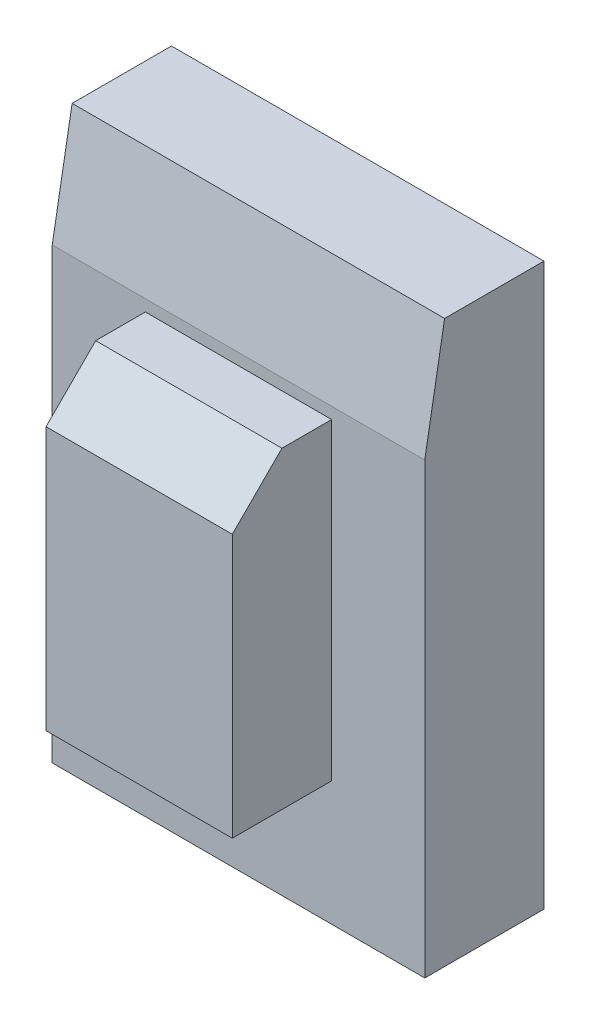
SolidWorks part; units mm, degrees
material "ABS"
ref_plane "Front Plane" through (0, 0, 0) normal (0, 0, 1) x (1, 0, 0)
ref_plane "Top Plane" through (0, 0, 0) normal (0, 1, 0) x (1, 0, 0)
ref_plane "Right Plane" through (0, 0, 0) normal (1, 0, 0) x (0, 0, -1)
sketch "Sketch1" plane through (0, 0, 0) normal (0, 0, 1) x (1, 0, 0)
  line L1 (0, 0) -> (9.525, 0)
  line L2 (0, 0) -> (0, -14.351)
  line L3 (0, -14.351) -> (9.525, -14.351)
  line L4 (9.525, 0) -> (9.525, -14.351)
  dimension "D1" = 14.351
  dimension "D2" = 9.525
extrude "Boss-Extrude1" add sketch "Sketch1" along normal blind 3.048
sketch "Sketch2" plane through (0, 0, 3.048) normal (0, 0, 1) x (1, 0, 0)
  line L1 (2.3813, -3.175) -> (7.1438, -3.175)
  line L3 (2.3813, -11.176) -> (7.1438, -11.176)
  line L6 (9.525, 0) -> (0, 0) construction
  line L7 (0, -14.351) -> (9.525, -14.351) construction
  line L8 (2.3813, -3.175) -> (2.3813, -11.176)
  line L9 (0, 0) -> (0, -14.351) construction
  line L10 (7.1438, -11.176) -> (7.1438, -3.175)
  line L11 (9.525, -14.351) -> (9.525, 0) construction
  dimension "D1" = 3.175
  dimension "D2" = 3.175
  dimension "D3" = 2.3813
  dimension "D4" = 2.3812
extrude "Boss-Extrude2" add sketch "Sketch2" along normal blind 2.54
chamfer "Chamfer1" distance 1.27 angle 45 1 edges at (4.7625, -3.175, 5.588)
chamfer "Chamfer2" distance 0.508 angle 80 1 edges at (4.7625, 0, 3.048)
